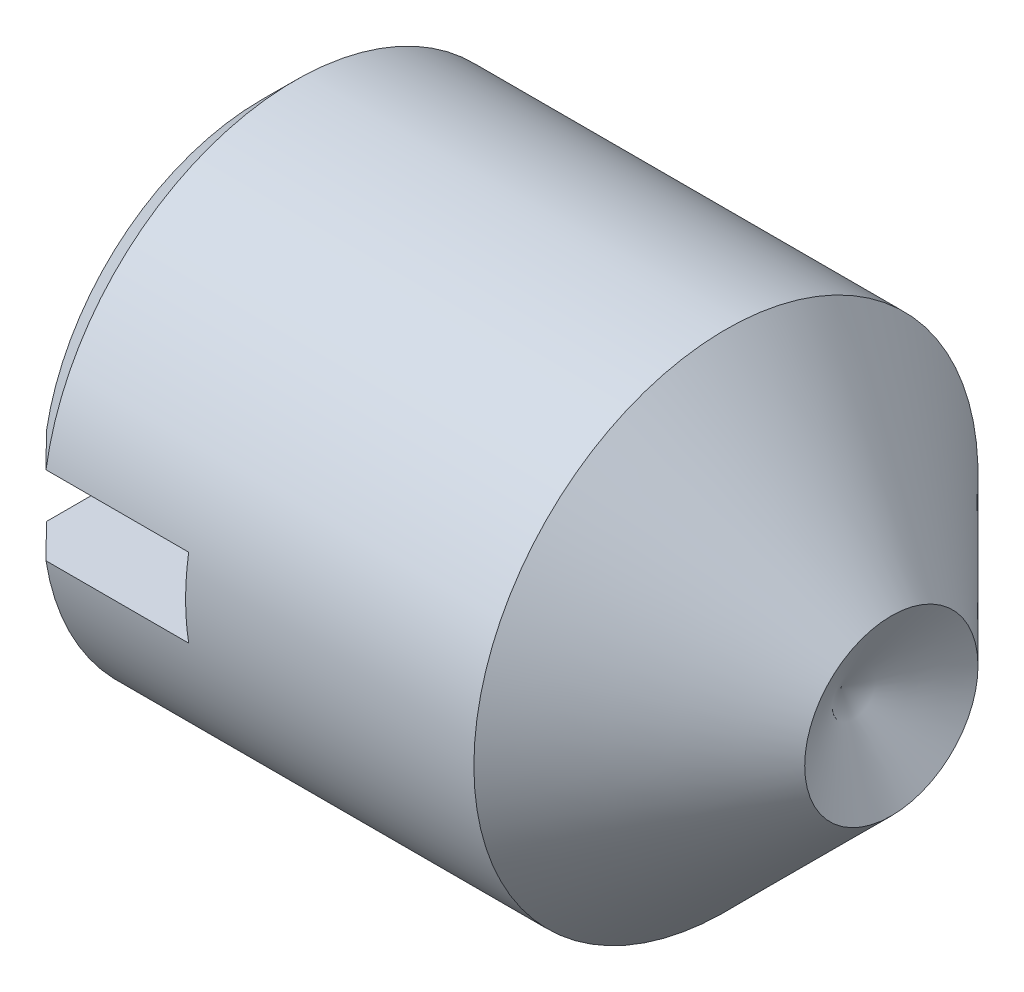
SolidWorks part; units mm, degrees
ref_plane "前视" through (0, 0, 0) normal (0, 0, 1) x (1, 0, 0)
ref_plane "上视" through (0, 0, 0) normal (0, 1, 0) x (1, 0, 0)
ref_plane "右视" through (0, 0, 0) normal (1, 0, 0) x (0, 0, -1)
sketch "尺寸草图" plane through (0, 0, 0) normal (0, 0, 1) x (1, 0, 0)
  line L0 (0, 0) -> (2, 0) construction
  point P3 (1.45, 0)
  point P4 (0.25, 0)
  point P5 (0.56, 0)
  point P6 (1.65, 0)
  point P7 (1.6, 0)
  dimension "l" = 2
  dimension "d" = 1.6
  dimension "P" = 0.35
  dimension "dz" = 0.55
  dimension "n" = 0.25
  dimension "t" = 0.56
sketch "草图2" plane through (0, 0, 0) normal (0, 0, 1) x (1, 0, 0)
  line L0 (0, 0) -> (2, 0)
  line L1 (2, 0) -> (2, 0.275)
  line L2 (2, 0.275) -> (1.475, 0.8)
  line L3 (1.475, 0.8) -> (0.1072, 0.8)
  line L4 (0.1072, 0.8) -> (0, 0.6928)
  line L5 (0, 0.6928) -> (0, 0)
  line L6 (5.2493, 0) -> (6.7321, 0) construction
  dimension "D1" = 45
  dimension "d" = 1.6
  dimension "df" = 1.3856
  dimension "dz" = 0.55
  dimension "D2" = 45
  dimension "l" = 2
revolve "基体-旋转" add sketch "草图2"
cosmetic thread "装饰螺纹线1"
extrude "切除-拉伸1" cut sketch "草图3" against normal mid plane 100
sketch "草图3" plane through (0, 0, 0) normal (0, 0, 1) x (1, 0, 0)
  line L0 (0, 0.6928) -> (0, -0.6928) construction
  line L1 (0, -0.125) -> (0.56, -0.125)
  line L2 (0, -0.125) -> (0, 0.125)
  line L3 (0, 0.125) -> (0.56, 0.125)
  line L4 (0.56, -0.125) -> (0.56, 0.125)
  point P6 (0, 0)
  dimension "n" = 0.25
  dimension "t" = 0.56
sketch "草图5" plane through (0, 0, 0) normal (0, 0, 1) x (1, 0, 0)
  line L0 (2, 0) -> (1.8412, 0)
  line L1 (5.2493, 0) -> (6.7321, 0) construction
  line L2 (1.8412, 0) -> (2, -0.275)
  line L3 (2, -0.275) -> (2, 0)
  line L5 (2, -0.275) -> (2, 0.275) construction
  line L6 (7.7233, 0) -> (8.1308, 0) construction
  dimension "D1" = 60
  dimension "D2" = 0.55
revolve "切除-旋转2" cut sketch "草图5" angle 360 about L6
